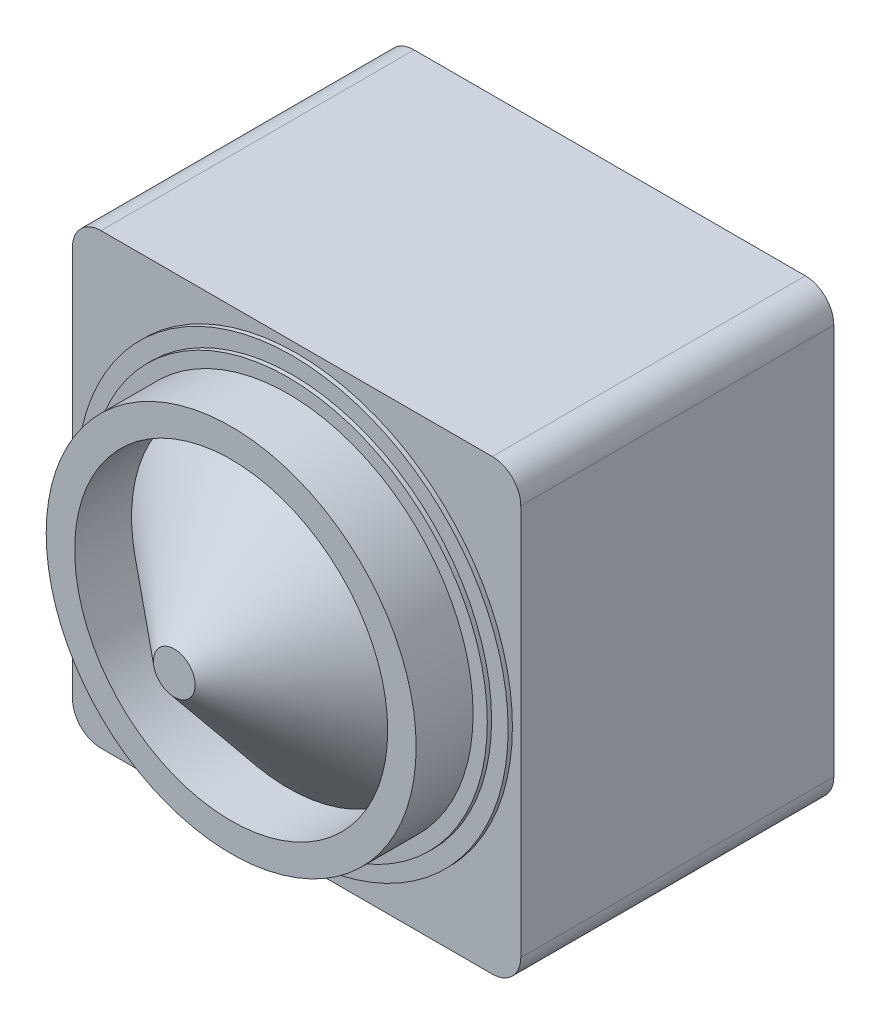
SolidWorks part; units mm, degrees
ref_plane "Front Plane" through (0, 0, 0) normal (0, 0, 1) x (1, 0, 0)
ref_plane "Top Plane" through (0, 0, 0) normal (0, 1, 0) x (1, 0, 0)
ref_plane "Right Plane" through (0, 0, 0) normal (1, 0, 0) x (0, 0, -1)
sketch "Sketch1" plane through (0, 0, 0) normal (0, 0, 1) x (1, 0, 0)
  line L1 (0, 0) -> (31.5, 0)
  line L2 (0, 0) -> (0, 31.5)
  line L3 (0, 31.5) -> (31.5, 31.5)
  line L4 (31.5, 0) -> (31.5, 31.5)
extrude "Boss-Extrude1" add sketch "Sketch1" along normal blind 22 contours L1 L4 L3 L2
fillet "Fillet2" radius 2 4 edges at (0, 0, 11) (31.5, 0, 11) (0, 31.5, 11) (31.5, 31.5, 11)
sketch "Sketch2" plane through (0, 0, 22) normal (0, 0, 1) x (1, 0, 0)
  line L0 (0.5858, 30.9142) -> (30.9142, 0.5858) construction
  line L1 (30.9142, 0.5858) -> (30.9142, 30.9142) construction
  line L2 (30.9142, 30.9142) -> (0.5858, 0.5858) construction
  arc A0 (2, 31.5) -> (0, 29.5) centre (2, 29.5) ccw construction
  arc A1 (29.5, 0) -> (31.5, 2) centre (29.5, 2) ccw construction
  arc A2 (31.5, 29.5) -> (29.5, 31.5) centre (29.5, 29.5) ccw construction
  arc A3 (0, 2) -> (2, 0) centre (2, 2) ccw construction
  circle A4 centre (15.75, 15.75) radius 15.1642
  point P18 (15.75, 15.75)
extrude "Boss-Extrude2" add sketch "Sketch2" along normal blind 0.3
sketch "Sketch3" plane through (0, 0, 22.3) normal (0, 0, 1) x (1, 0, 0)
  circle A0 centre (15.75, 15.75) radius 14
extrude "Boss-Extrude3" add sketch "Sketch3" along normal blind 0.3 contours A0
sketch "Sketch4" plane through (0, 0, 22.6) normal (0, 0, 1) x (1, 0, 0)
  circle A0 centre (15.75, 15.75) radius 13
  circle A1 centre (15.75, 15.75) radius 11
extrude "Boss-Extrude5" add sketch "Sketch4" along normal blind 4 contours A0 | A1
sketch "Sketch6" plane through (0, 0, 22.6) normal (0, 0, 1) x (1, 0, 0)
  circle A0 centre (15.75, 15.75) radius 11
extrude "Boss-Extrude6" add sketch "Sketch6" along normal blind 8 draft 50
